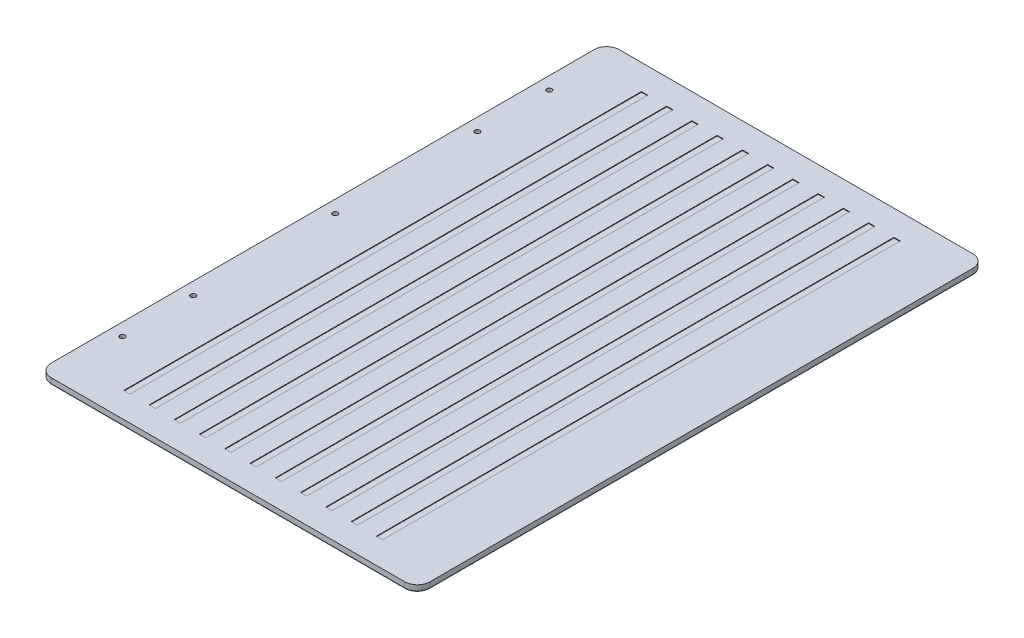
SolidWorks part; units mm, degrees
ref_plane "Front Plane" through (0, 0, 0) normal (0, 0, 1) x (1, 0, 0)
ref_plane "Top Plane" through (0, 0, 0) normal (0, 1, 0) x (1, 0, 0)
ref_plane "Right Plane" through (0, 0, 0) normal (1, 0, 0) x (0, 0, -1)
sketch "Sketch1" plane through (0, 0, 0) normal (0, 1, 0) x (1, 0, 0)
  line L1 (-150, -225) -> (150, -225)
  line L2 (-150, -225) -> (-150, 225)
  line L3 (-150, 225) -> (150, 225)
  line L4 (150, -225) -> (150, 225)
  line L5 (-150, -225) -> (150, 225) construction
  line L6 (-150, 225) -> (150, -225) construction
  point P0 (0, 0)
  dimension "D1" = 300
  dimension "D2" = 450
extrude "Boss-Extrude1" add sketch "Sketch1" along normal blind 5
sketch "Sketch2" plane through (0, 5, 0) normal (0, 1, 0) x (1, 0, 0)
  line L0 (-140, 225) -> (-140, -225) construction
  line L1 (150, 225) -> (-150, 225) construction
  line L2 (-150, -225) -> (150, -225) construction
  line L3 (-150, 225) -> (-150, -225) construction
  circle A0 centre (-140, 0) radius 2
  circle A1 centre (-140, 112.5) radius 2
  circle A2 centre (-140, -112.5) radius 2
  circle A3 centre (-140, 169.5) radius 2
  circle A4 centre (-140, -168.5) radius 2
  dimension "D2" = 112.5
  dimension "D5" = 56
  dimension "D6" = 4
  dimension "D7" = 4
  dimension "D8" = 4
  dimension "D9" = 4
  dimension "D10" = 4
  dimension "D1" = 10
  dimension "D3" = 112.5
  dimension "D4" = 57
extrude "Cut-Extrude1" cut sketch "Sketch2" against normal through all
fillet "Fillet2" radius 10 4 edges at (-150, 2.5, -225) (150, 2.5, -225) (150, 2.5, 225) (-150, 2.5, 225)
fillet "Fillet1" radius 1 8 edges at (-150, 0, 0) (150, 0, 0) (0, 0, 225) (0, 0, -225) (147.0711, 0, 222.0711) (-147.0711, 0, 222.0711) (-147.0711, 0, -222.0711) (147.0711, 0, -222.0711)
sketch "Sketch3" plane through (0, 5, 0) normal (0, 1, 0) x (1, 0, 0)
  line L0 (-150, 0) -> (150, 0) construction
  line L1 (-150, 215) -> (-150, -215) construction
  line L2 (150, -215) -> (150, 215) construction
  line L3 (-130, 225) -> (-130, -225) construction
  line L4 (140, 225) -> (-140, 225) construction
  line L5 (-140, -225) -> (140, -225) construction
  line L6 (-150, 205) -> (150, 205) construction
  line L7 (-150, -205) -> (150, -205) construction
  line L8 (130, -225) -> (130, 225) construction
  line L9 (17.5, -205) -> (17.5, 205)
  line L10 (-2.5, -205) -> (2.5, -205)
  line L11 (-2.5, -205) -> (-2.5, 205)
  line L12 (-2.5, 205) -> (2.5, 205)
  line L13 (2.5, -205) -> (2.5, 205)
  line L14 (-2.5, -205) -> (2.5, 205) construction
  line L15 (-2.5, 205) -> (2.5, -205) construction
  line L16 (17.5, -205) -> (22.5, -205)
  line L17 (22.5, -205) -> (22.5, 205)
  line L18 (17.5, 205) -> (22.5, 205)
  line L19 (37.5, -205) -> (37.5, 205)
  line L20 (37.5, -205) -> (42.5, -205)
  line L21 (42.5, -205) -> (42.5, 205)
  line L22 (37.5, 205) -> (42.5, 205)
  line L23 (57.5, -205) -> (57.5, 205)
  line L24 (57.5, -205) -> (62.5, -205)
  line L25 (62.5, -205) -> (62.5, 205)
  line L26 (57.5, 205) -> (62.5, 205)
  line L27 (77.5, -205) -> (77.5, 205)
  line L28 (77.5, -205) -> (82.5, -205)
  line L29 (82.5, -205) -> (82.5, 205)
  line L30 (77.5, 205) -> (82.5, 205)
  line L31 (97.5, -205) -> (97.5, 205)
  line L32 (97.5, -205) -> (102.5, -205)
  line L33 (102.5, -205) -> (102.5, 205)
  line L34 (97.5, 205) -> (102.5, 205)
  line L35 (-22.5, -205) -> (-22.5, 205)
  line L36 (-22.5, -205) -> (-17.5, -205)
  line L37 (-17.5, -205) -> (-17.5, 205)
  line L38 (-22.5, 205) -> (-17.5, 205)
  line L39 (-42.5, -205) -> (-42.5, 205)
  line L40 (-42.5, -205) -> (-37.5, -205)
  line L41 (-37.5, -205) -> (-37.5, 205)
  line L42 (-42.5, 205) -> (-37.5, 205)
  line L43 (-62.5, -205) -> (-62.5, 205)
  line L44 (-62.5, -205) -> (-57.5, -205)
  line L45 (-57.5, -205) -> (-57.5, 205)
  line L46 (-62.5, 205) -> (-57.5, 205)
  line L47 (-82.5, -205) -> (-82.5, 205)
  line L48 (-82.5, -205) -> (-77.5, -205)
  line L49 (-77.5, -205) -> (-77.5, 205)
  line L50 (-82.5, 205) -> (-77.5, 205)
  line L51 (-102.5, -205) -> (-102.5, 205)
  line L52 (-102.5, -205) -> (-97.5, -205)
  line L53 (-97.5, -205) -> (-97.5, 205)
  line L54 (-102.5, 205) -> (-97.5, 205)
  point P18 (0, 0)
  dimension "D1" = 20
  dimension "D2" = 20
  dimension "D3" = 20
  dimension "D4" = 20
  dimension "D5" = 5
  dimension "D6" = 6
  dimension "D7" = 6
extrude "Cut-Extrude2" cut sketch "Sketch3" against normal blind 0.5
